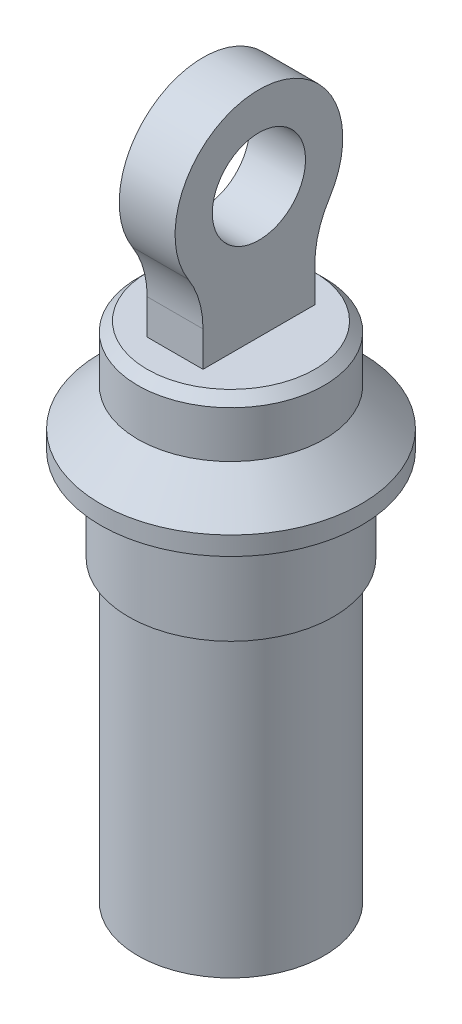
SolidWorks part; units mm, degrees
material "PBT General Purpose"
ref_plane "Front Plane" through (0, 0, 0) normal (0, 0, 1) x (1, 0, 0)
ref_plane "Top Plane" through (0, 0, 0) normal (0, 1, 0) x (1, 0, 0)
ref_plane "Right Plane" through (0, 0, 0) normal (1, 0, 0) x (0, 0, -1)
sketch "Sketch1" plane through (0, 0, 0) normal (0, 1, 0) x (1, 0, 0)
  circle A0 centre (0, 0) radius 5
  dimension "D1" = 10
extrude "Boss-Extrude1" add sketch "Sketch1" along normal blind 8
sketch "Sketch2" plane through (0, 8, 0) normal (0, 1, 0) x (1, 0, 0)
  circle A0 centre (0, 0) radius 5.5
  dimension "D1" = 11
extrude "Boss-Extrude2" add sketch "Sketch2" along normal blind 5
sketch "Sketch3" plane through (0, 13, 0) normal (0, 1, 0) x (1, 0, 0)
  circle A0 centre (0, 0) radius 7
  dimension "D1" = 14
extrude "Boss-Extrude3" add sketch "Sketch3" along normal blind 1
sketch "Sketch47" plane through (0, 0, 0) normal (1, 0, 0) x (0, 0, -1)
  line L0 (0, 14) -> (0, 19)
  line L1 (7, 14) -> (-7, 14) construction
  line L2 (0, 19) -> (5, 19)
  line L3 (5, 19) -> (5, 16)
  line L4 (5, 16) -> (7, 14)
  line L5 (0, 14) -> (7, 14)
  dimension "D1" = 5
  dimension "D2" = 3
  dimension "D3" = 2
revolve "Revolve1" add sketch "Sketch47" angle 360 about L0
chamfer "Chamfer2" distance 0.5 angle 45 1 edges at (0, 19, -5)
sketch "Sketch48" plane through (0, 19, 0) normal (0, 1, 0) x (1, 0, 0)
  line L1 (-1.4982, -3) -> (1.4982, -3)
  line L2 (-1.4982, -3) -> (-1.4982, 3)
  line L3 (-1.4982, 3) -> (1.4982, 3)
  line L4 (1.4982, -3) -> (1.4982, 3)
  line L5 (-1.4982, -3) -> (1.4982, 3) construction
  line L6 (-1.4982, 3) -> (1.4982, -3) construction
  point P0 (0, 0)
  dimension "D1" = 6
  dimension "D2" = 2.9963
  dimension "D3" = 2.9963
extrude "Boss-Extrude7" add sketch "Sketch48" along normal blind 7
sketch "Sketch50" plane through (1.4982, 0, 0) normal (1, 0, 0) x (0, 0, -1)
  line L0 (-3, 26) -> (3, 26) construction
  circle A0 centre (0, 26) radius 4.5
  circle A1 centre (0, 26) radius 4.5
  dimension "D1" = 9
extrude "Boss-Extrude9" add sketch "Sketch50" against normal blind 2.99 contours A0
sketch "Sketch51" plane through (-1.4982, 0, 0) normal (-1, 0, 0) x (0, 0, 1)
  line L0 (-3, 26) -> (3, 26) construction
  circle A0 centre (0, 26) radius 4.5
extrude "Boss-Extrude10" add sketch "Sketch51" against normal blind 2.99
sketch "Sketch52" plane through (-1.4982, 0, 0) normal (-1, 0, 0) x (0, 0, 1)
  circle A1 centre (0, 26) radius 2.5
  point P6 (4.2455, 24.508)
  dimension "D1" = 5
extrude "Cut-Extrude1" cut sketch "Sketch52" against normal blind 4
sketch "Sketch53" plane through (0, 0, 0) normal (0, -1, 0) x (1, 0, 0)
sketch "Sketch56" plane through (0, 8, 0) normal (0, -1, 0) x (1, 0, 0)
  circle A0 centre (0, 0) radius 5
extrude "Boss-Extrude11" add sketch "Sketch56" along normal blind 16
sketch "Sketch57" plane through (0, -8, 0) normal (0, -1, 0) x (1, 0, 0)
  circle A0 centre (0, 0) radius 3.25
  dimension "D1" = 6.5
extrude "Cut-Extrude7" cut sketch "Sketch57" against normal blind 21
sketch "Sketch59" plane through (0, -8, 0) normal (0, -1, 0) x (-1, 0, 0)
  circle A0 centre (0, 0) radius 3.5
  dimension "D1" = 7
extrude "Cut-Extrude10" cut sketch "Sketch59" against normal blind 26
cosmetic thread "Cosmetic Thread1" parameters "D1"=5, "D2"=8
fillet "Fillet1" radius 5 2 edges at (0, 22.6459, 3) (0, 22.6459, -3)
